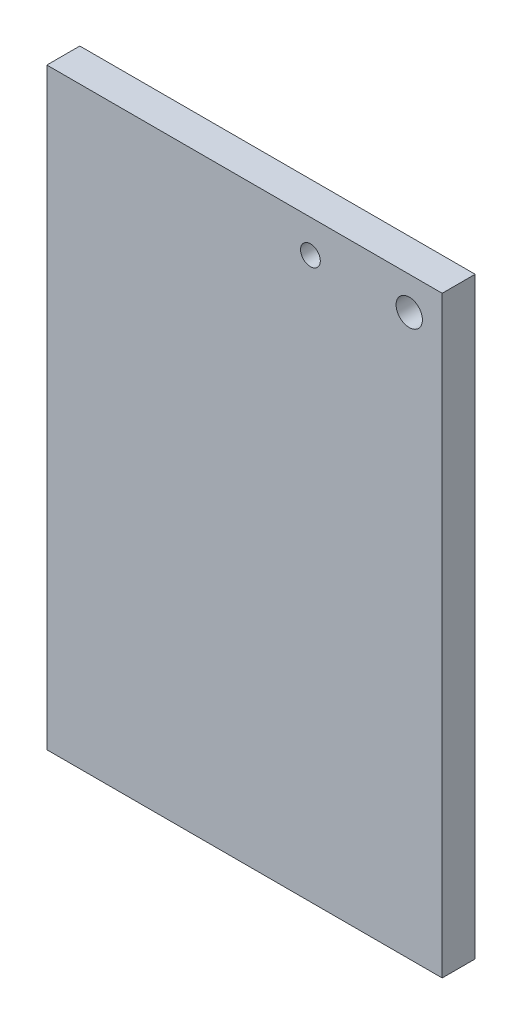
SolidWorks part; units mm, degrees
ref_plane "Plan de face" through (0, 0, 0) normal (0, 0, 1) x (1, 0, 0)
ref_plane "Plan de dessus" through (0, 0, 0) normal (0, 1, 0) x (1, 0, 0)
ref_plane "Plan de droite" through (0, 0, 0) normal (1, 0, 0) x (0, 0, -1)
sketch "Esquisse1" plane through (0, 0, 0) normal (0, 0, 1) x (1, 0, 0)
  line L1 (0, 0) -> (60, 0)
  line L2 (0, 0) -> (0, -90)
  line L3 (0, -90) -> (60, -90)
  line L4 (60, 0) -> (60, -90)
  circle A0 centre (55, -5) radius 2
  circle A1 centre (40, -5) radius 1.5
  dimension "D3" = 4
  dimension "D4" = 3
  dimension "D1" = 60
  dimension "D2" = 90
  dimension "D5" = 15
  dimension "D6" = 5
  dimension "D7" = 5
  dimension "D8" = 5
extrude "Boss.-Extru.1" add sketch "Esquisse1" along normal blind 5
